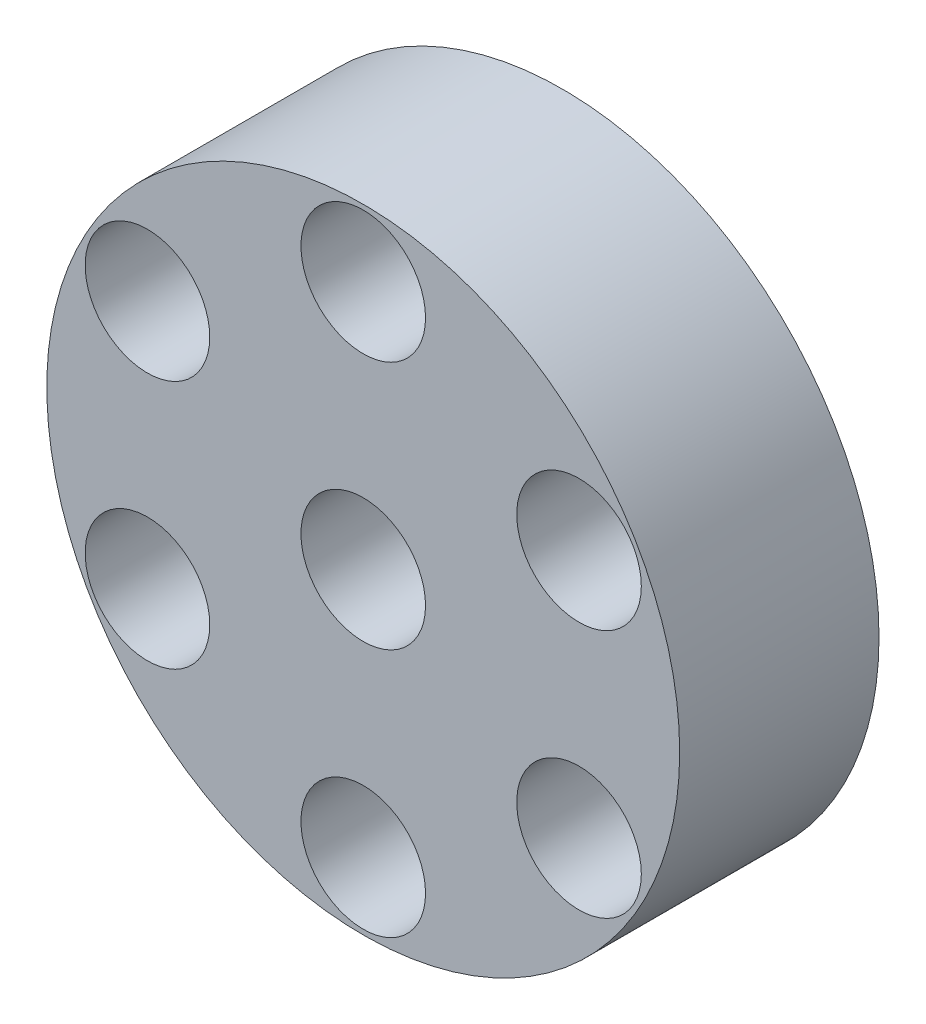
SolidWorks part; units mm, degrees
ref_plane "Front Plane" through (0, 0, 0) normal (0, 0, 1) x (1, 0, 0)
ref_plane "Top Plane" through (0, 0, 0) normal (0, 1, 0) x (1, 0, 0)
ref_plane "Right Plane" through (0, 0, 0) normal (1, 0, 0) x (0, 0, -1)
sketch "Sketch1" plane through (0, 0, 0) normal (0, 0, 1) x (1, 0, 0)
  circle A0 centre (0, 0) radius 12.7
  dimension "D1" = 25.4
extrude "Boss-Extrude1" add sketch "Sketch1" along normal blind 8
sketch "Sketch2" plane through (0, 0, 8) normal (0, 0, 1) x (1, 0, 0)
  circle A0 centre (0, 10) radius 2.5
  circle A1 centre (8.6603, 5) radius 2.5
  circle A2 centre (8.6603, -5) radius 2.5
  circle A3 centre (0, -10) radius 2.5
  circle A4 centre (-8.6603, -5) radius 2.5
  circle A5 centre (-8.6603, 5) radius 2.5
  circle A6 centre (0, 0) radius 2.5
  point P16 (0, 0)
  dimension "D1" = 5
  dimension "D5" = 5
  dimension "D2" = 10
  dimension "D3" = 0
  dimension "D6" = 5
  dimension "D7" = 8.6603
  dimension "D4" = 6
extrude "Cut-Extrude1" cut sketch "Sketch2" against normal blind 8
